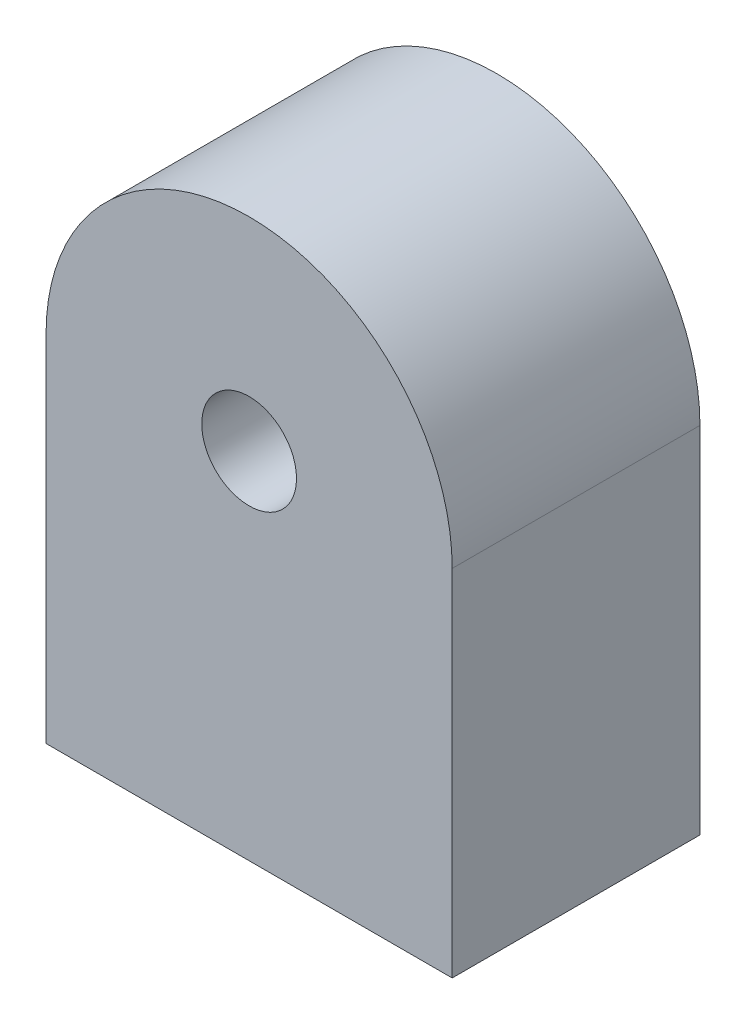
SolidWorks part; units mm, degrees
ref_plane "Plan de face" through (0, 0, 0) normal (0, 0, 1) x (1, 0, 0)
ref_plane "Plan de dessus" through (0, 0, 0) normal (0, 1, 0) x (1, 0, 0)
ref_plane "Plan de droite" through (0, 0, 0) normal (1, 0, 0) x (0, 0, -1)
sketch "Esquisse1" plane through (0, 0, 0) normal (0, 0, 1) x (1, 0, 0)
  line L2 (-15, 13.1) -> (-15, -13.1)
  line L3 (-15, -13.1) -> (15, -13.1)
  line L4 (15, 13.1) -> (15, -13.1)
  line L5 (-15, 13.1) -> (15, -13.1) construction
  line L6 (-15, -13.1) -> (15, 13.1) construction
  arc A0 (-15, 13.1) -> (15, 13.1) centre (0, 13.1) cw
  point P0 (0, 0)
  dimension "D1" = 30
  dimension "D2" = 26.2
extrude "Boss.-Extru.1" add sketch "Esquisse1" along normal blind 18.3
sketch "Esquisse2" plane through (0, -13.1, 0) normal (0, -1, 0) x (1, 0, 0)
  line L0 (0, 0) -> (0, 5.68) construction
  line L1 (-15, 0) -> (15, 0) construction
  line L2 (-7.25, 9.23) -> (7.25, 9.23)
  line L3 (-7.25, 9.23) -> (-7.25, 2.13)
  line L4 (-7.25, 2.13) -> (7.25, 2.13)
  line L5 (7.25, 9.23) -> (7.25, 2.13)
  line L6 (-7.25, 9.23) -> (7.25, 2.13) construction
  line L7 (-7.25, 2.13) -> (7.25, 9.23) construction
  dimension "D1" = 2.13
  dimension "D2" = 7.1
  dimension "D3" = 14.5
extrude "Enlèv. mat.-Extru.1" cut sketch "Esquisse2" against normal blind 1
sketch "Esquisse3" plane through (0, -12.1, 0) normal (0, -1, 0) x (1, 0, 0)
  line L0 (0, 2.13) -> (0, 5.13) construction
  line L1 (-7.25, 2.13) -> (7.25, 2.13) construction
  line L2 (-4.76, 5.45) -> (-5.4, 5.45)
  line L3 (-0.32, 5.45) -> (0.32, 5.45)
  line L4 (-0.32, 5.45) -> (-0.32, 4.81)
  line L5 (-0.32, 4.81) -> (0.32, 4.81)
  line L6 (0.32, 5.45) -> (0.32, 4.81)
  line L7 (-0.32, 5.45) -> (0.32, 4.81) construction
  line L8 (-0.32, 4.81) -> (0.32, 5.45) construction
  line L9 (2.22, 5.45) -> (2.22, 4.81)
  line L10 (2.22, 5.45) -> (2.86, 5.45)
  line L11 (2.86, 5.45) -> (2.86, 4.81)
  line L12 (2.22, 4.81) -> (2.86, 4.81)
  line L13 (4.76, 5.45) -> (4.76, 4.81)
  line L14 (4.76, 5.45) -> (5.4, 5.45)
  line L15 (5.4, 5.45) -> (5.4, 4.81)
  line L16 (4.76, 4.81) -> (5.4, 4.81)
  line L17 (-5.4, 5.45) -> (-5.4, 4.81)
  line L18 (-4.76, 4.81) -> (-5.4, 4.81)
  line L19 (-4.76, 5.45) -> (-4.76, 4.81)
  line L20 (-2.22, 5.45) -> (-2.86, 5.45)
  line L21 (-2.86, 5.45) -> (-2.86, 4.81)
  line L22 (-2.22, 4.81) -> (-2.86, 4.81)
  line L23 (-2.22, 5.45) -> (-2.22, 4.81)
  dimension "D1" = 3
  dimension "D2" = 0.64
  dimension "D3" = 0.64
  dimension "D5" = 2.54
  dimension "D4" = 3
extrude "Boss.-Extru.2" add sketch "Esquisse3" along normal blind 1
sketch "Esquisse4" plane through (0, 0, 18.3) normal (0, 0, 1) x (1, 0, 0)
  line L0 (0, -13.1) -> (0, 13.1) construction
  line L1 (-15, -13.1) -> (15, -13.1) construction
  circle A0 centre (0, 13.1) radius 3.5
  dimension "D2" = 7
  dimension "D1" = 26.2
extrude "Enlèv. mat.-Extru.2" cut sketch "Esquisse4" against normal through all
